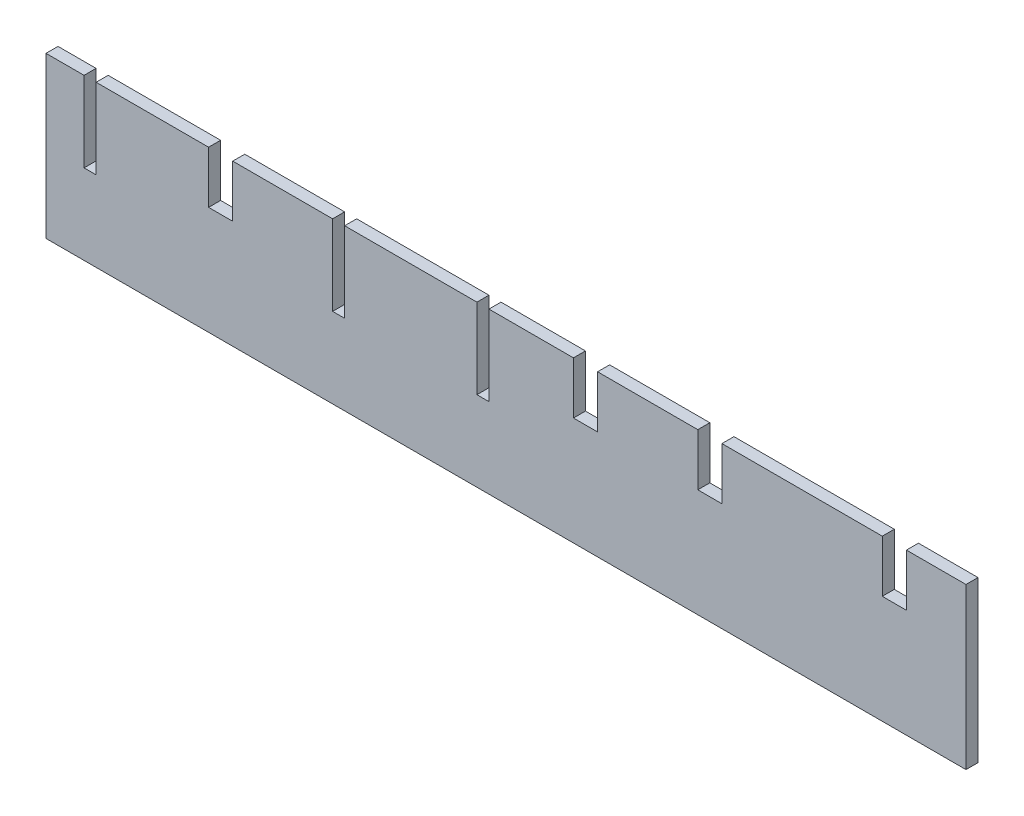
SolidWorks part; units mm, degrees
ref_plane "Front Plane" through (0, 0, 0) normal (0, 0, 1) x (1, 0, 0)
ref_plane "Top Plane" through (0, 0, 0) normal (0, 1, 0) x (1, 0, 0)
ref_plane "Right Plane" through (0, 0, 0) normal (1, 0, 0) x (0, 0, -1)
sketch "Sketch1" plane through (0, 0, 0) normal (0, 0, 1) x (1, 0, 0)
  line L3 (-79, -40) -> (380, -40)
  line L4 (380, 40) -> (380, -40)
  line L5 (-380, 40) -> (380, -40) construction
  line L6 (-380, -40) -> (380, 40) construction
  line L8 (246.2, 14) -> (246.2, 40)
  line L13 (2.12, 14) -> (2.12, 40)
  line L14 (14.16, 14) -> (14.16, 40)
  line L15 (184.16, 14) -> (184.16, 40)
  line L16 (196.2, 14) -> (196.2, 40)
  line L21 (-79, 40) -> (2.12, 40)
  line L23 (258.24, 40) -> (258.24, 14)
  line L24 (258.24, 14) -> (246.2, 14)
  line L25 (338.24, 40) -> (338.24, 14)
  line L26 (350.28, 40) -> (380, 40)
  line L27 (350.28, 40) -> (350.28, 14)
  line L28 (-79, 40) -> (-79, -40)
  line L29 (338.24, 14) -> (350.28, 14)
  line L30 (2.12, 14) -> (14.16, 14)
  line L31 (14.16, 40) -> (184.16, 40)
  line L32 (184.16, 14) -> (196.2, 14)
  line L33 (196.2, 40) -> (246.2, 40)
  line L34 (258.24, 40) -> (338.24, 40)
  point P0 (0, 0)
  dimension "D1" = 80
  dimension "D2" = 459
  dimension "D3" = 26
  dimension "D4" = 26
  dimension "D11" = 12.04
  dimension "D12" = 170
  dimension "D13" = 12.04
  dimension "D14" = 50
  dimension "D15" = 12.04
  dimension "D16" = 80
  dimension "D17" = 12.04
extrude "Boss-Extrude1" add sketch "Sketch1" along normal blind 6
sketch "Sketch2" plane through (0, 0, 0) normal (0, 0, -1) x (-1, 0, 0)
  line L2 (-70, 0) -> (-64, 0)
  line L5 (54, 0) -> (60, 0)
  line L10 (-70, 0) -> (-70, 40)
  line L11 (-184.16, 40) -> (-14.16, 40) construction
  line L12 (-70, 40) -> (-64, 40)
  line L13 (-64, 40) -> (-64, 0)
  line L15 (54, 0) -> (54, 40)
  line L16 (-2.12, 40) -> (79, 40) construction
  line L17 (54, 40) -> (60, 40)
  line L18 (60, 40) -> (60, 0)
  line L19 (-380, -40) -> (-380, 40) construction
  line L21 (-142, 40) -> (-136, 40)
  line L22 (-142, 40) -> (-142, 0)
  line L23 (-142, 0) -> (-136, 0)
  line L24 (-136, 40) -> (-136, 0)
  dimension "D1" = 40
  dimension "D2" = 6
  dimension "D3" = 6
  dimension "D4" = 310
  dimension "D6" = 6
  dimension "D8" = 40
  dimension "D10" = 238
extrude "Cut-Extrude1" cut sketch "Sketch2" against normal blind 10
